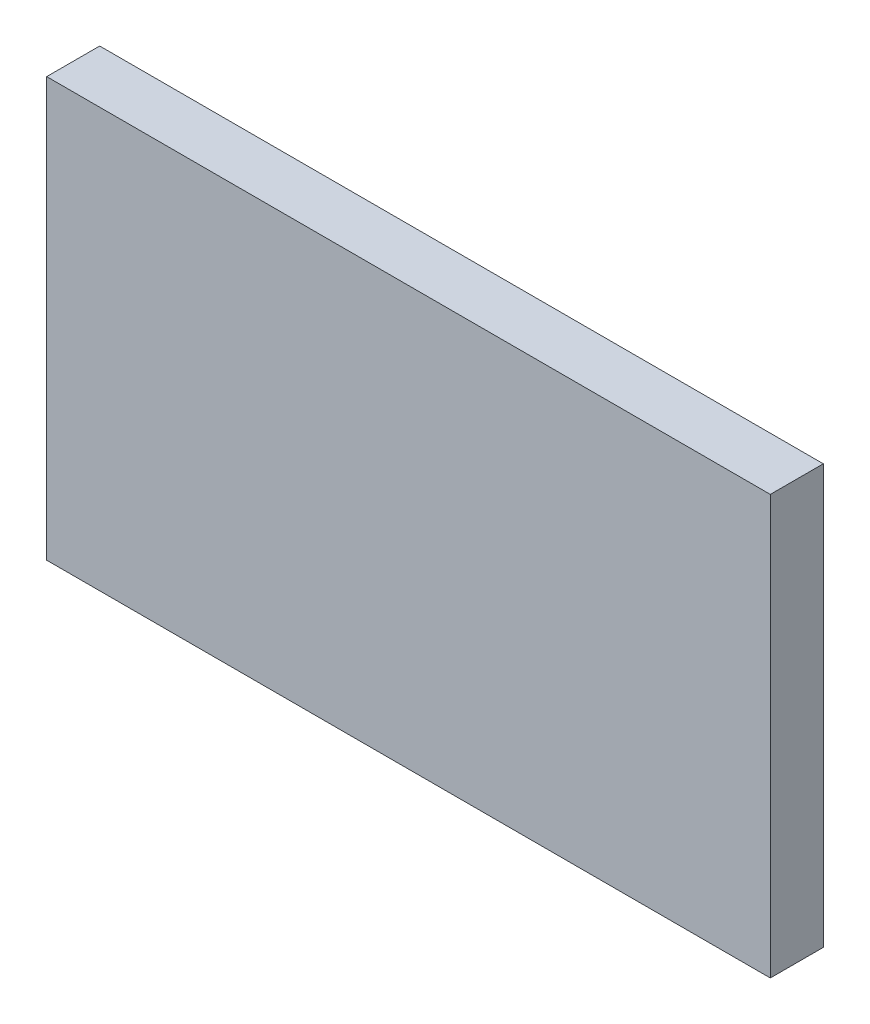
SolidWorks part; units mm, degrees
ref_plane "Front Plane" through (0, 0, 0) normal (0, 0, 1) x (1, 0, 0)
ref_plane "Top Plane" through (0, 0, 0) normal (0, 1, 0) x (1, 0, 0)
ref_plane "Right Plane" through (0, 0, 0) normal (1, 0, 0) x (0, 0, -1)
sketch "Sketch1" plane through (0, 0, 0) normal (0, 0, 1) x (1, 0, 0)
  line L0 (-228.854, -132.461) -> (228.854, -132.461)
  line L1 (-228.854, -132.461) -> (-228.854, 132.461)
  line L2 (228.854, -132.461) -> (228.854, 132.461)
  line L3 (-228.854, 132.461) -> (228.854, 132.461)
  line L4 (-228.854, -132.461) -> (228.854, 132.461) construction
  line L5 (228.854, -132.461) -> (-228.854, 132.461) construction
  point P1 (0, 0)
  dimension "D1" = 457.708
  dimension "D2" = 264.922
extrude "Boss-Extrude1" add sketch "Sketch1" along normal blind 33.528
sketch "Sketch2" plane through (0, 0, 33.528) normal (0, 0, 1) x (1, 0, 0)
  point P0 (0, 0)
